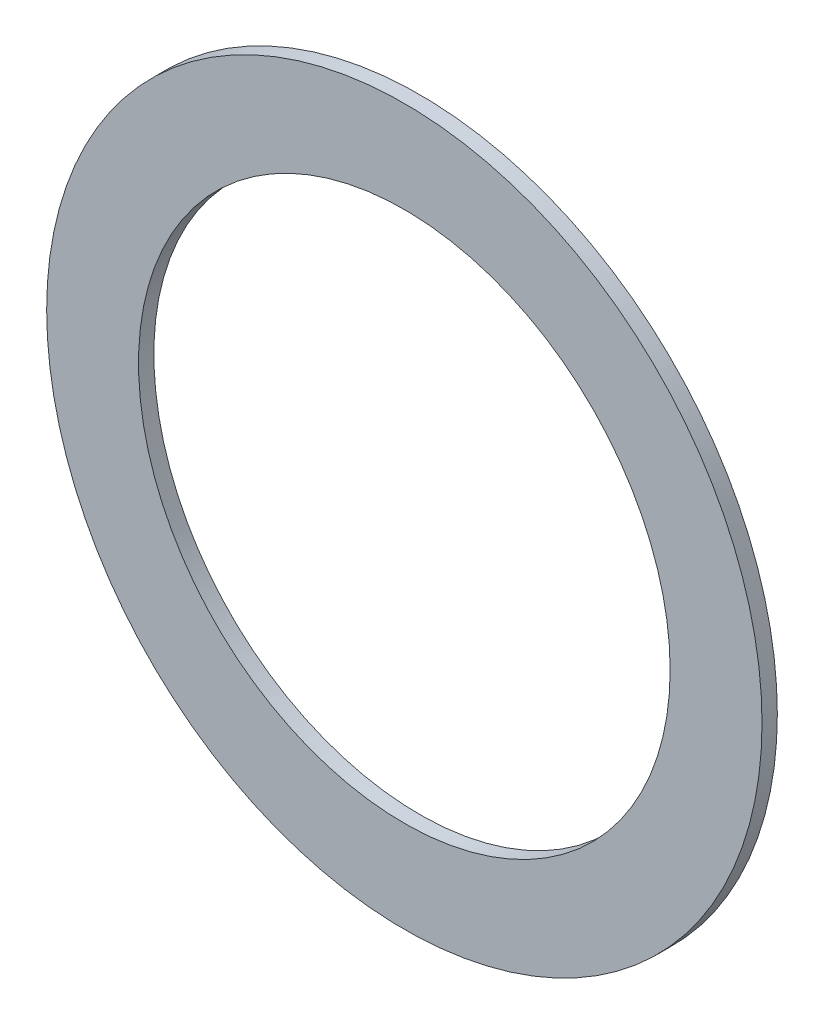
SolidWorks part; units mm, degrees
material "1060 Alloy"
ref_plane "Front Plane" through (0, 0, 0) normal (0, 0, 1) x (1, 0, 0)
ref_plane "Top Plane" through (0, 0, 0) normal (0, 1, 0) x (1, 0, 0)
ref_plane "Right Plane" through (0, 0, 0) normal (1, 0, 0) x (0, 0, -1)
sketch "Sketch1" plane through (0, 0, 0) normal (0, 0, 1) x (1, 0, 0)
  circle A0 centre (0, 0) radius 116.8
  dimension "D1" = 233.6
extrude "Extrude-Thin1" add sketch "Sketch1" along normal mid plane 5 thin thin type one direction reverse wall 30
